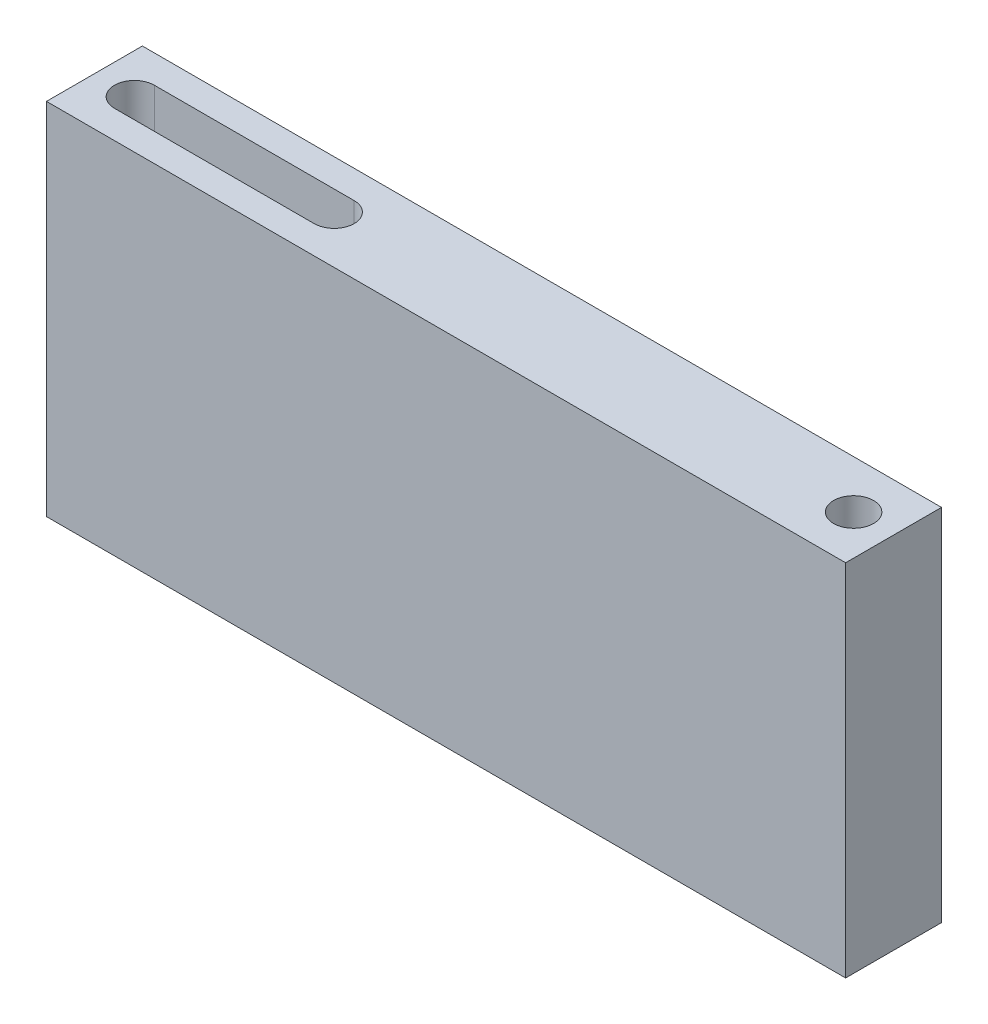
SolidWorks part; units mm, degrees
ref_plane "Front Plane" through (0, 0, 0) normal (0, 0, 1) x (1, 0, 0)
ref_plane "Top Plane" through (0, 0, 0) normal (0, 1, 0) x (1, 0, 0)
ref_plane "Right Plane" through (0, 0, 0) normal (1, 0, 0) x (0, 0, -1)
sketch "Sketch3" plane through (0, 0, 0) normal (0, 0, 1) x (1, 0, 0)
  line L1 (0, 0) -> (100, 0)
  line L2 (0, 0) -> (0, 45)
  line L3 (0, 45) -> (100, 45)
  line L4 (100, 0) -> (100, 45)
  dimension "D1" = 100
  dimension "D2" = 45
extrude "Boss-Extrude2" add sketch "Sketch3" along normal blind 12 contours L1 L4 L3 L2
sketch "Sketch4" plane through (0, 0, 0) normal (0, -1, 0) x (1, 0, 0)
  line L0 (30, 6) -> (5, 6) construction
  line L1 (30, 3.5) -> (5, 3.5)
  line L2 (30, 8.5) -> (5, 8.5)
  line L3 (0, 12) -> (0, 0) construction
  line L4 (100, 12) -> (100, 0) construction
  arc A0 (30, 3.5) -> (30, 8.5) centre (30, 6) ccw
  arc A1 (5, 8.5) -> (5, 3.5) centre (5, 6) ccw
  circle A2 centre (95, 6) radius 2.5
  point P2 (17.5, 6)
  point P11 (0, 6)
  point P12 (0, 0)
  point P15 (100, 6)
  dimension "D2" = 5
  dimension "D3" = 2.5
  dimension "D1" = 25
  dimension "D4" = 65
  dimension "D5" = 5
extrude "Cut-Extrude1" cut sketch "Sketch4" against normal through all
